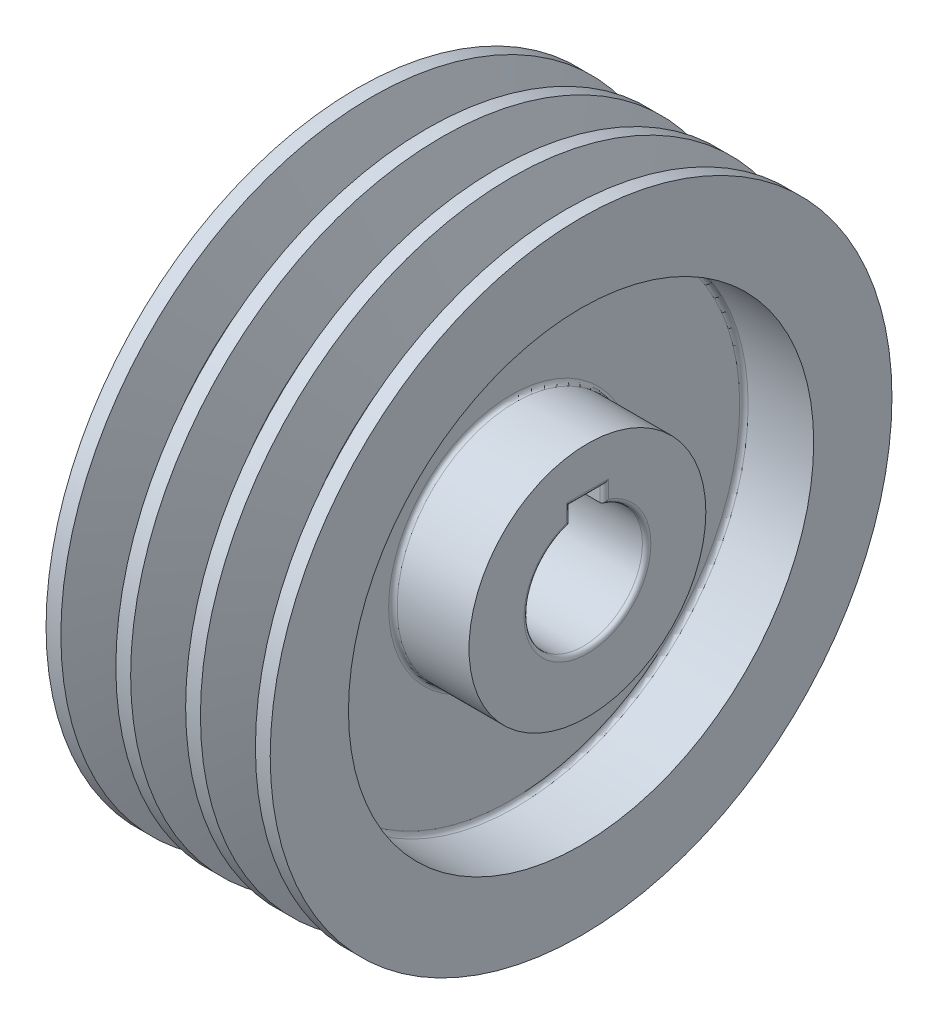
SolidWorks part; units mm, degrees
ref_plane "前视基准面" through (0, 0, 0) normal (0, 0, 1) x (1, 0, 0)
ref_plane "上视基准面" through (0, 0, 0) normal (0, 1, 0) x (1, 0, 0)
ref_plane "右视基准面" through (0, 0, 0) normal (1, 0, 0) x (0, 0, -1)
sketch "草图1" plane through (0, 0, 0) normal (0, 0, 1) x (1, 0, 0)
  line L0 (-4.5546, 0) -> (7.0103, 0) construction
  line L1 (-0.855, 3.5384) -> (-1.111, 2.7563)
  line L2 (-1.111, 2.7563) -> (0.112, 2.7563)
  line L3 (0.112, 2.7563) -> (-0.1582, 3.5384)
  line L4 (-0.1582, 3.5384) -> (-0.855, 3.5384)
  line L5 (0, -610.5758) -> (0, 650.6712) construction
  line L7 (-7010.4, 22402.8) -> (-8077.2, 22402.8)
  line L8 (-743.256, 18592.8) -> (743.256, 18592.8)
  line L9 (743.256, 18592.8) -> (1981.2, 22402.8)
  line L10 (1981.2, 22402.8) -> (3048, 22402.8)
  line L11 (3048, 22402.8) -> (4285.944, 18592.8)
  line L12 (4285.944, 18592.8) -> (5772.456, 18592.8)
  line L13 (5772.456, 18592.8) -> (7010.4, 22402.8)
  line L14 (7010.4, 22402.8) -> (8077.2, 22402.8)
  line L15 (-5772.456, 18592.8) -> (-7010.4, 22402.8)
  line L16 (-4285.944, 18592.8) -> (-5772.456, 18592.8)
  line L17 (-3048, 22402.8) -> (-4285.944, 18592.8)
  line L18 (-1981.2, 22402.8) -> (-3048, 22402.8)
  line L19 (-743.256, 18592.8) -> (-1981.2, 22402.8)
  line L20 (0.1582, 3.5384) -> (0.855, 3.5384)
  line L21 (-0.112, 2.7563) -> (0.1582, 3.5384)
  line L22 (1.111, 2.7563) -> (-0.112, 2.7563)
  line L23 (0.855, 3.5384) -> (1.111, 2.7563)
  line L24 (-8077.2, 22402.8) -> (-8077.2, 0)
  line L25 (8077.2, 22402.8) -> (8077.2, 0)
  line L26 (-8077.2, 0) -> (8077.2, 0)
  point P17 (5029.2, 18592.8)
  point P27 (0, 9296.4)
  dimension "D1" = 37185.6
  dimension "D2" = 36
  dimension "D4" = 3810
  dimension "D5" = 18
  dimension "D6" = 3048
  dimension "D7" = 3962.4
revolve "旋转3" add sketch "草图1" angle 360 about L0
sketch "草图2" plane through (0, 0, 0) normal (1, 0, 0) x (0, 0, -1)
  circle A0 centre (0, 0) radius 8534.4
  dimension "D1" = 17068.8
extrude "凸台-拉伸1" add sketch "草图2" along normal mid plane 17068.8
sketch "草图3" plane through (8534.4, 0, 0) normal (1, 0, 0) x (0, 0, -1)
  line L0 (0, 0) -> (0, -9467.8333) construction
  line L2 (-1219.2, 4089.3211) -> (-1219.2, 5273.04)
  line L3 (-1219.2, 5273.04) -> (1219.2, 5273.04)
  line L4 (1219.2, 4089.3211) -> (1219.2, 5273.04)
  arc A0 (-1219.2, 4089.3211) -> (1219.2, 4089.3211) centre (0, 0) ccw
  point P3 (0, 4267.2)
  dimension "D1" = 8534.4
  dimension "D2" = 5273.04
  dimension "D3" = 2438.4
extrude "切除-拉伸1" cut sketch "草图3" against normal through all
sketch "草图6" plane through (8077.2, 0, 0) normal (1, 0, 0) x (0, 0, -1)
  circle A0 centre (0, 0) radius 8534.4
  circle A1 centre (0, 0) radius 16764
  dimension "D1" = 33528
extrude "切除-拉伸3" cut sketch "草图6" against normal blind 5029.2
mirror "镜向1" about plane through (0, 0, 0) normal (1, 0, 0) of "切除-拉伸3"
fillet "圆角1" radius 304.8 4 edges at (8534.4, 5273.04, 0) (8534.4, 4681.1806, 1219.2) (8534.4, 4681.1806, -1219.2) (8534.4, -4267.2, 0)
fillet "圆角2" radius 304.8 4 edges at (-8534.4, 4681.1806, 1219.2) (-8534.4, 4681.1806, -1219.2) (-8534.4, 5273.04, 0) (-8534.4, -4267.2, 0)
fillet "圆角3" radius 304.8 1 edges at (3048, 0, -16764)
fillet "圆角4" radius 304.8 3 edges at (-3048, 0, -8534.4) (-3048, 0, -16764) (3048, 0, -8534.4)
